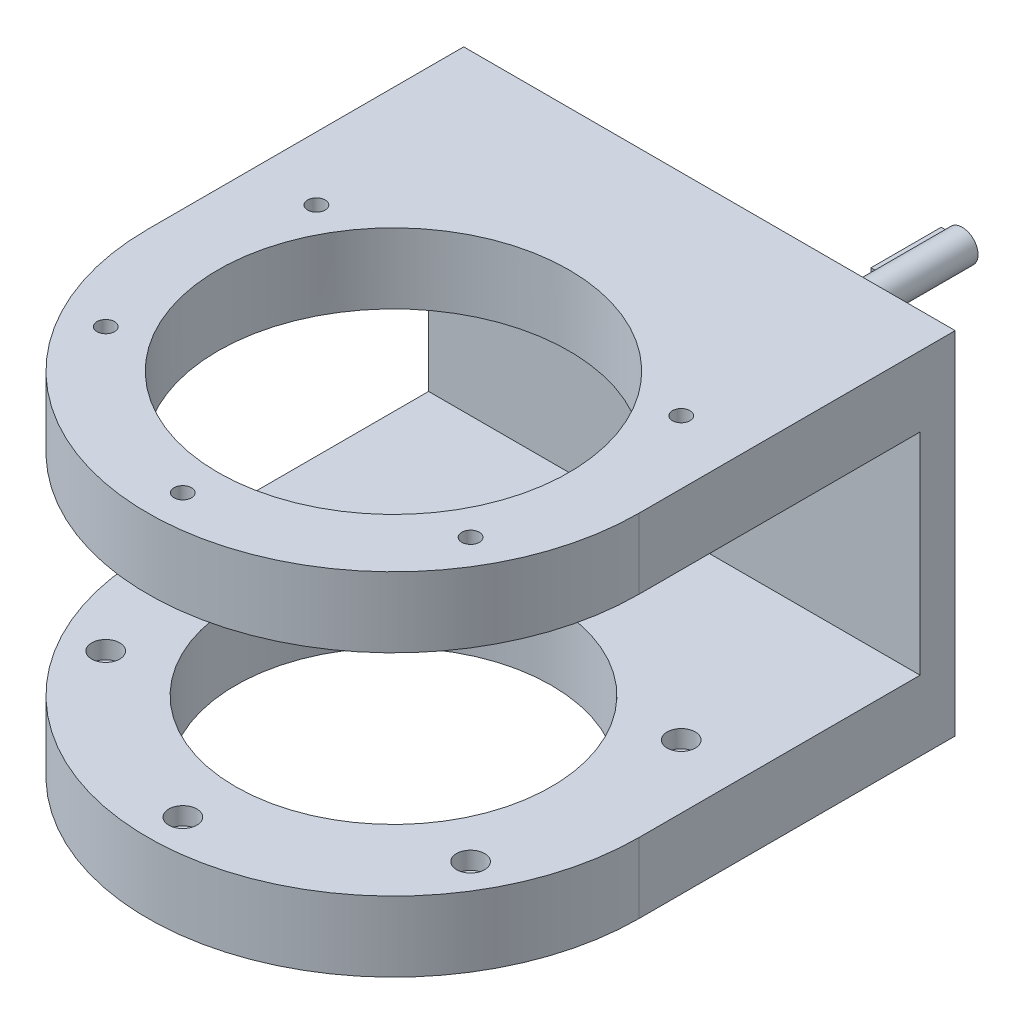
SolidWorks part; units mm, degrees
ref_plane "前视基准面" through (0, 0, 0) normal (0, 0, 1) x (1, 0, 0)
ref_plane "上视基准面" through (0, 0, 0) normal (0, 1, 0) x (1, 0, 0)
ref_plane "右视基准面" through (0, 0, 0) normal (1, 0, 0) x (0, 0, -1)
other "Configuration Table"
sketch "草图1" plane through (0, 0, 0) normal (0, 0, 1) x (1, 0, 0)
  circle A1 centre (0, -0.5933) radius 25
  dimension "D1" = 50
extrude "凸台-拉伸1" add sketch "草图1" along normal blind 22
sketch "草图2" plane through (0, 0, 22) normal (0, 0, 1) x (1, 0, 0)
  line L1 (-70, -50) -> (70, -50)
  line L2 (-70, -50) -> (-70, 50)
  line L3 (-70, 50) -> (70, 50)
  line L4 (70, -50) -> (70, 50)
  line L5 (-70, -50) -> (70, 50) construction
  line L6 (-70, 50) -> (70, -50) construction
  point P0 (0, 0)
  dimension "D1" = 140
  dimension "D2" = 100
extrude "凸台-拉伸2" add sketch "草图2" along normal blind 10
sketch "草图4" plane through (0, 0, 32) normal (0, 0, 1) x (1, 0, 0)
  line L0 (70, -50) -> (70, 50) construction
  line L1 (-70, 50) -> (70, 50)
  line L2 (-70, 50) -> (-70, 30)
  line L3 (-70, 30) -> (70, 30)
  line L4 (70, 50) -> (70, 30)
  line L5 (-70, 50) -> (-70, -50) construction
  line L7 (-70, -30) -> (70, -30)
  line L8 (-70, -30) -> (-70, -50)
  line L9 (-70, -50) -> (70, -50)
  line L10 (70, -30) -> (70, -50)
  line L11 (-70, -50) -> (70, -50) construction
  dimension "D1" = 20
  dimension "D2" = 20
  dimension "D3" = 0
extrude "凸台-拉伸3" add sketch "草图4" along normal blind 150
sketch "草图6" plane through (0, 50, 0) normal (0, 1, 0) x (1, 0, 0)
  line L0 (-70, -182) -> (-70, -22) construction
  line L1 (70, -182) -> (-70, -182) construction
  line L2 (-70, -112) -> (-70, -182)
  line L3 (-70, -182) -> (0, -182)
  line L4 (0, -182) -> (70, -182)
  line L5 (70, -182) -> (70, -112)
  line L6 (70, -182) -> (70, -22) construction
  circle A0 centre (0, -112) radius 70
  line M4 (-70, -22) -> (-70, -182)
  line M5 (-70, -182) -> (70, -182)
  line M6 (70, -182) -> (70, -22)
  dimension "D1" = 70
extrude "切除-拉伸1" cut sketch "草图6" against normal blind 150 contours A0 M4 M5 | A0 M5 M6
sketch "草图7" plane through (0, 0, 0) normal (0, 0, -1) x (-1, 0, 0)
  circle A0 centre (0, 0) radius 4.5
  dimension "D1" = 9
sketch "草图8" plane through (0, 50, 0) normal (0, 1, 0) x (1, 0, 0)
  arc A0 (-70, -112) -> (70, -112) centre (0, -112) ccw construction
  arc A1 (-70, -112) -> (70, -112) centre (0, -112) ccw
  circle A2 centre (0, -112) radius 50
  dimension "D1" = 100
extrude "切除-拉伸3" cut sketch "草图8" against normal up to next contours A2
sketch "草图9" plane through (0, -50, 0) normal (0, -1, 0) x (1, 0, 0)
  arc A0 (70, 112) -> (-70, 112) centre (0, 112) ccw construction
  arc A1 (70, 112) -> (-70, 112) centre (0, 112) ccw
  circle A2 centre (0, 112) radius 45
  dimension "D1" = 90
extrude "切除-拉伸4" cut sketch "草图9" against normal up to next contours A2
extrude "凸台-拉伸4" add sketch "草图7" along normal blind 50
sketch "草图10" plane through (0, -50, 0) normal (0, -1, 0) x (1, 0, 0)
  line L3 (70, 22) -> (70, 112)
  line L4 (-70, 112) -> (-70, 22)
  line L5 (-70, 22) -> (70, 22)
  line L6 (70, 22) -> (70, 112)
  line L7 (-70, 112) -> (-70, 22)
  line L8 (-70, 22) -> (70, 22)
  arc A1 (70, 112) -> (-70, 112) centre (0, 112) ccw
  arc A2 (70, 112) -> (-70, 112) centre (0, 112) ccw
  circle A3 centre (0, 112) radius 60
  circle A4 centre (0, 172) radius 2.5
  circle A5 centre (51.9615, 142) radius 2.5
  circle A6 centre (51.9615, 82) radius 2.5
  circle A7 centre (0, 52) radius 2.5
  circle A8 centre (-51.9615, 82) radius 2.5
  circle A9 centre (-51.9615, 142) radius 2.5
  point P21 (0, 112)
  dimension "D2" = 120
  dimension "D3" = 5
  dimension "D1" = 0
  dimension "D4" = 6
extrude "切除-拉伸5" cut sketch "草图10" against normal up to next contours A9 | A8 | A7 | A6 | A5 | A4
sketch "草图11" plane through (0, -30, 0) normal (0, 1, 0) x (1, 0, 0)
  line L3 (70, -112) -> (70, -32)
  line L4 (70, -32) -> (-70, -32)
  line L5 (-70, -32) -> (-70, -112)
  line L6 (70, -112) -> (70, -32)
  line L7 (70, -32) -> (-70, -32)
  line L8 (-70, -32) -> (-70, -112)
  arc A1 (-70, -112) -> (70, -112) centre (0, -112) ccw
  arc A2 (-70, -112) -> (70, -112) centre (0, -112) ccw
  circle A3 centre (0, -172) radius 4
  circle A4 centre (-51.9615, -142) radius 4
  circle A5 centre (-51.9615, -82) radius 4
  circle A6 centre (0, -52) radius 4
  circle A7 centre (51.9615, -82) radius 4
  circle A8 centre (51.9615, -142) radius 4
  point P20 (0, -112)
  circle M8 centre (0, -52) radius 2.5
  dimension "D2" = 8
  dimension "D1" = 0
  dimension "D3" = 6
extrude "切除-拉伸7" cut sketch "草图11" against normal blind 5 contours A6 M8 | A7 | A5 | A4 | A3 | A8
sketch "草图12" plane through (0, 50, 0) normal (0, 1, 0) x (1, 0, 0)
  circle A0 centre (51.9615, -142) radius 4 construction
  circle A1 centre (51.9615, -82) radius 4 construction
  circle A2 centre (0, -52) radius 4 construction
  circle A3 centre (0, -172) radius 4 construction
  circle A4 centre (-51.9615, -142) radius 4 construction
  circle A5 centre (-51.9615, -82) radius 4 construction
  circle A6 centre (51.9615, -142) radius 4
  circle A7 centre (51.9615, -82) radius 4
  circle A8 centre (0, -52) radius 4
  circle A9 centre (0, -172) radius 4
  circle A10 centre (-51.9615, -142) radius 4
  circle A11 centre (-51.9615, -82) radius 4
sketch "草图13" plane through (0, 50, 0) normal (0, 1, 0) x (1, 0, 0)
  circle A0 centre (51.9615, -82) radius 2.5 construction
  circle A1 centre (51.9615, -142) radius 2.5 construction
  circle A2 centre (0, -172) radius 2.5 construction
  circle A3 centre (-51.9615, -142) radius 2.5 construction
  circle A4 centre (-51.9615, -82) radius 2.5 construction
  circle A5 centre (51.9615, -82) radius 2.5
  circle A6 centre (51.9615, -142) radius 2.5
  circle A7 centre (0, -172) radius 2.5
  circle A8 centre (-51.9615, -142) radius 2.5
  circle A9 centre (-51.9615, -82) radius 2.5
extrude "切除-拉伸9" cut sketch "草图13" against normal up to next
sketch "草图14" plane through (0, 30, 0) normal (0, -1, 0) x (1, 0, 0)
  line L3 (70, 32) -> (70, 112)
  line L4 (-70, 112) -> (-70, 32)
  line L5 (-70, 32) -> (70, 32)
  line L6 (70, 32) -> (70, 112)
  line L7 (-70, 112) -> (-70, 32)
  line L8 (-70, 32) -> (70, 32)
  circle A0 centre (0, 172) radius 4 construction
  arc A1 (70, 112) -> (-70, 112) centre (0, 112) ccw
  arc A2 (70, 112) -> (-70, 112) centre (0, 112) ccw
  circle A3 centre (-51.9615, 142) radius 4 construction
  circle A4 centre (-51.9615, 82) radius 4 construction
  circle A5 centre (0, 52) radius 4 construction
  circle A6 centre (51.9615, 82) radius 4 construction
  circle A7 centre (51.9615, 142) radius 4 construction
  circle A8 centre (0, 172) radius 4
  circle A9 centre (-51.9615, 142) radius 4
  circle A10 centre (-51.9615, 82) radius 4
  circle A11 centre (0, 52) radius 4
  circle A12 centre (51.9615, 82) radius 4
  circle A13 centre (51.9615, 142) radius 4
  dimension "D1" = 0
extrude "切除-拉伸11" cut sketch "草图14" against normal blind 5 contours A9 | A8 | A13 | A12 | A10 | A11
sketch "草图15" plane through (0, -50, 0) normal (0, -1, 0) x (1, 0, 0)
sketch "草图16" plane through (0, 0, 0) normal (0, 0, -1) x (-1, 0, 0)
  line L1 (0, -1.5) -> (6, -1.5)
  line L2 (0, -1.5) -> (0, 1.5)
  line L3 (0, 1.5) -> (6, 1.5)
  line L4 (6, -1.5) -> (6, 1.5)
  dimension "D1" = 3
  dimension "D2" = 6
extrude "凸台-拉伸5" add sketch "草图16" along normal blind 50
sketch "草图17" plane through (0, 0, 0) normal (0, 0, -1) x (-1, 0, 0)
  line L0 (6, 1.5) -> (4.2426, 1.5) construction
  line L1 (6, 1.5) -> (4.2426, 1.5)
  line L3 (4.2426, -1.5) -> (6, -1.5)
  line L4 (6, 1.5) -> (4.2426, 1.5)
  line L5 (6, -1.5) -> (6, 1.5)
  line L6 (4.2426, -1.5) -> (6, -1.5)
  line L7 (6, 1.5) -> (4.2426, 1.5)
  line L8 (6, -1.5) -> (6, 1.5)
  circle A0 centre (0, 0) radius 4.5
  arc A1 (4.2426, 1.5) -> (4.2426, -1.5) centre (0, 0) ccw
  arc A2 (4.2426, 1.5) -> (4.2426, -1.5) centre (0, 0) ccw
  line M6 (6, -1.5) -> (4.2426, -1.5)
  line M8 (4.2426, 1.5) -> (6, 1.5)
  line M9 (6, 1.5) -> (6, -1.5)
  dimension "D1" = 0
extrude "切除-拉伸12" cut sketch "草图17" along normal blind 30 contours A0 M6 M9 M8
